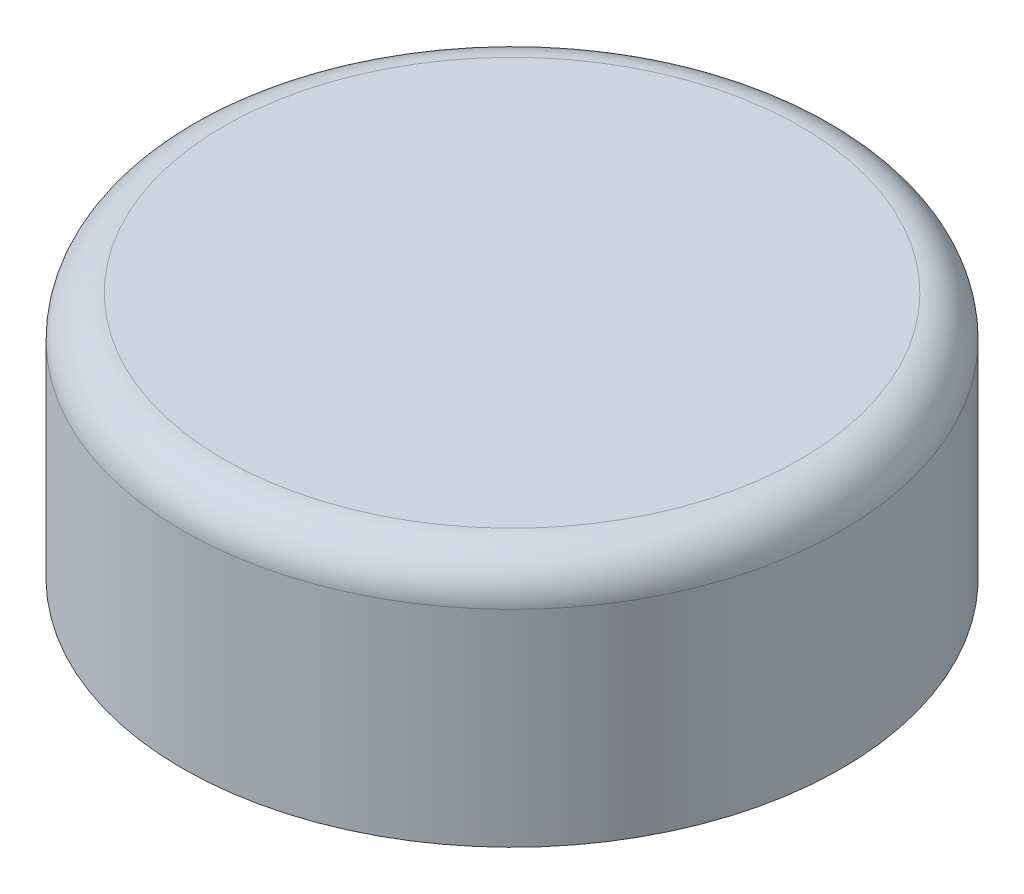
SolidWorks part; units mm, degrees
ref_plane "Front Plane" through (0, 0, 0) normal (0, 0, 1) x (1, 0, 0)
ref_plane "Top Plane" through (0, 0, 0) normal (0, 1, 0) x (1, 0, 0)
ref_plane "Right Plane" through (0, 0, 0) normal (1, 0, 0) x (0, 0, -1)
sketch "Sketch1" plane through (0, 0, 0) normal (0, 1, 0) x (1, 0, 0)
  circle A0 centre (0, 0) radius 4
  dimension "D1" = 8
extrude "Boss-Extrude1" add sketch "Sketch1" along normal blind 3
fillet "Fillet1" radius 0.5 1 edges at (0, 3, 4)
